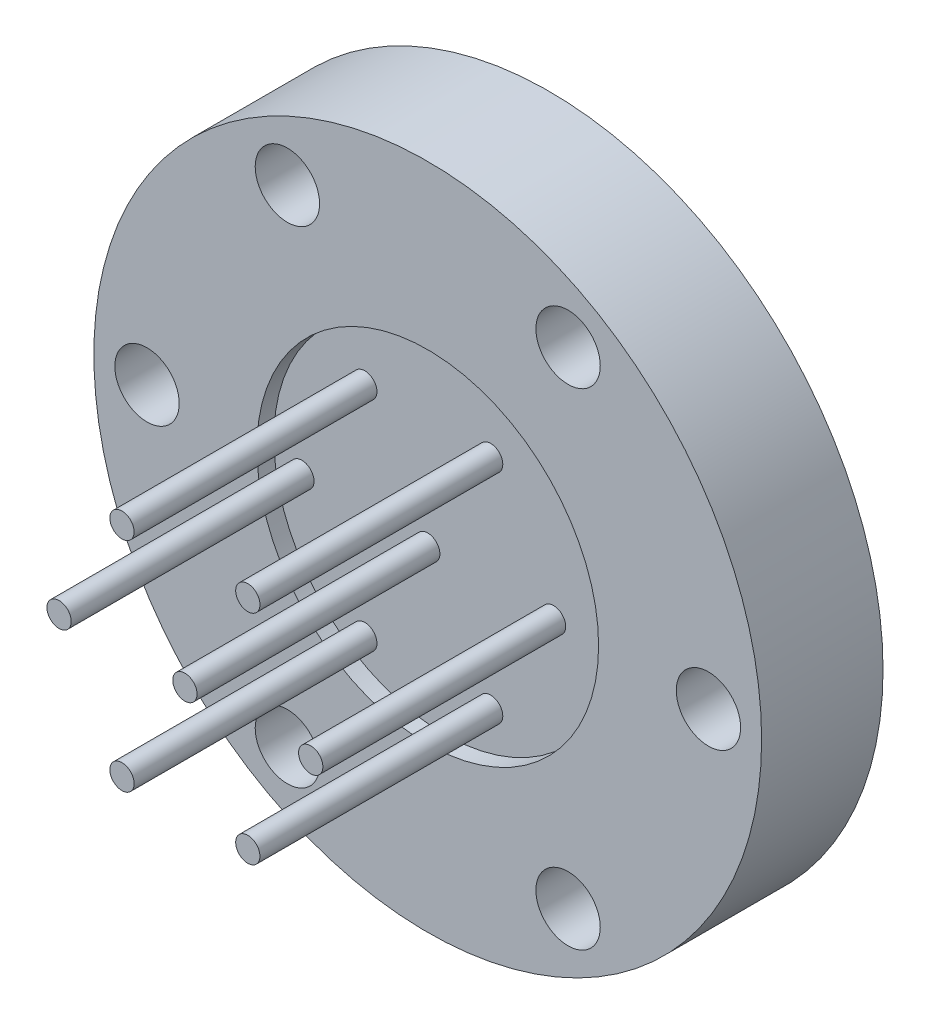
SolidWorks part; units mm, degrees
ref_plane "Front" through (0, 0, 0) normal (0, 0, 1) x (1, 0, 0)
ref_plane "Top" through (0, 0, 0) normal (0, 1, 0) x (1, 0, 0)
ref_plane "Right" through (0, 0, 0) normal (1, 0, 0) x (0, 0, -1)
sketch "Sketch1" plane through (0, 0, 0) normal (0, 0, 1) x (1, 0, 0)
  circle A0 centre (0, 0) radius 34.925
extrude "Extrude1" add sketch "Sketch1" along normal blind 12.7
sketch "Sketch2" plane through (0, 0, 0) normal (0, 0, -1) x (-1, 0, 0)
  circle A0 centre (0, 0) radius 23.0708
extrude "Cut-Extrude1" cut sketch "Sketch2" against normal blind 2
sketch "Sketch3" plane through (0, 0, 12.7) normal (0, 0, 1) x (1, 0, 0)
  circle A1 centre (0, 0) radius 1.27
  circle A2 centre (-6.5807, 11.3981) radius 1.27
  circle A3 centre (6.5807, 11.3981) radius 1.27
  circle A4 centre (13.1613, 0) radius 1.27
  circle A5 centre (6.5807, -11.3981) radius 1.27
  circle A6 centre (-6.5807, -11.3981) radius 1.27
  circle A7 centre (-13.1613, 0) radius 1.27
extrude "Extrude4" add sketch "Sketch3" along normal blind 25.4
sketch "Sketch4" plane through (0, 0, 12.7) normal (0, 0, 1) x (1, 0, 0)
  circle A0 centre (0, 0) radius 17.8731
extrude "Cut-Extrude2" cut sketch "Sketch4" against normal blind 1.778
sketch "Sketch5" plane through (0, 0, 0) normal (0, 0, -1) x (-1, 0, 0)
  line L1 (29.3624, 0) -> (14.6812, 25.4286)
  line L2 (14.6812, 25.4286) -> (-14.6812, 25.4286)
  line L3 (-14.6812, 25.4286) -> (-29.3624, 0)
  line L4 (-29.3624, 0) -> (-14.6812, -25.4286)
  line L5 (-14.6812, -25.4286) -> (14.6812, -25.4286)
  line L6 (14.6812, -25.4286) -> (29.3624, 0)
  circle A0 centre (0, 0) radius 25.4286 construction
  dimension "D1" = 58.7248
sketch "Sketch6" plane through (0, 0, 0) normal (0, 0, -1) x (-1, 0, 0)
  circle A0 centre (-14.6812, 25.4286) radius 3.3655
  circle A1 centre (14.6812, 25.4286) radius 3.3655
  circle A2 centre (29.3624, 0) radius 3.3655
  circle A3 centre (14.6812, -25.4286) radius 3.3655
  circle A4 centre (-14.6812, -25.4286) radius 3.3655
  circle A5 centre (-29.3624, 0) radius 3.3655
extrude "Cut-Extrude3" cut sketch "Sketch6" against normal through all
